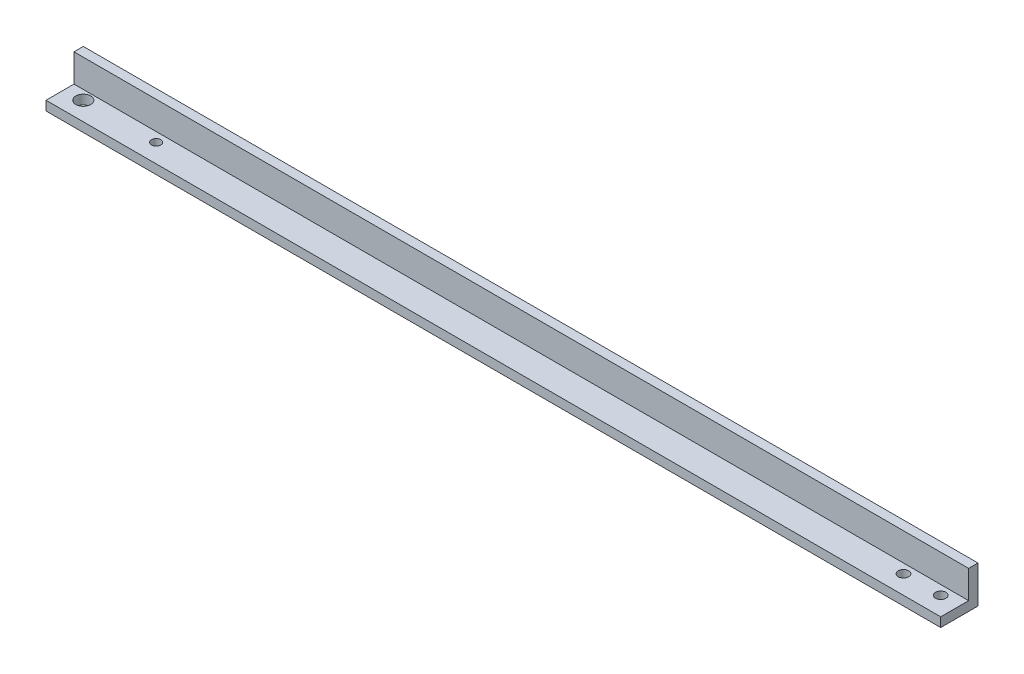
SolidWorks part; units mm, degrees
material "6061-T6 (SS)"
ref_plane "Front Plane" through (0, 0, 0) normal (0, 0, 1) x (1, 0, 0)
ref_plane "Top Plane" through (0, 0, 0) normal (0, 1, 0) x (1, 0, 0)
ref_plane "Right Plane" through (0, 0, 0) normal (1, 0, 0) x (0, 0, -1)
sketch "Sketch1" plane through (0, 0, 0) normal (1, 0, 0) x (0, 0, -1)
  line L0 (0, 0) -> (0, 19.05)
  line L1 (0, 19.05) -> (6.35, 19.05)
  line L2 (6.35, 19.05) -> (6.35, -6.35)
  line L3 (6.35, -6.35) -> (-19.05, -6.35)
  line L4 (-19.05, -6.35) -> (-19.05, 0)
  line L5 (-19.05, 0) -> (0, 0)
  dimension "D1" = 25.4
  dimension "D2" = 25.4
  dimension "D3" = 6.35
  dimension "D4" = 6.35
extrude "Boss-Extrude1" add sketch "Sketch1" along normal blind 609.6
sketch "Sketch2" plane through (0, -6.35, 0) normal (0, -1, 0) x (1, 0, 0)
  line L0 (0, 6.35) -> (609.6, 6.35) construction
  line L1 (0, 19.05) -> (0, -6.35) construction
  line L2 (304.8, 19.05) -> (304.8, -6.35) construction
  line L5 (609.6, 19.05) -> (609.6, -6.35) construction
  line L6 (609.6, 19.05) -> (0, 19.05) construction
  line L7 (609.6, -6.35) -> (0, -6.35) construction
  circle A0 centre (12.7, 6.35) radius 5.08
  circle A1 centre (62.357, 6.35) radius 3.175
  circle A10 centre (596.9, 6.35) radius 3.556
  circle A11 centre (571.5, 6.35) radius 3.556
  dimension "D1" = 10.16
  dimension "D2" = 6.35
  dimension "D3" = 12.7
  dimension "D4" = 49.657
  dimension "D6" = 7.112
  dimension "D7" = 12.7
  dimension "D8" = 25.4
  dimension "D5" = 7.112
extrude "Cut-Extrude1" cut sketch "Sketch2" against normal blind 914.4
